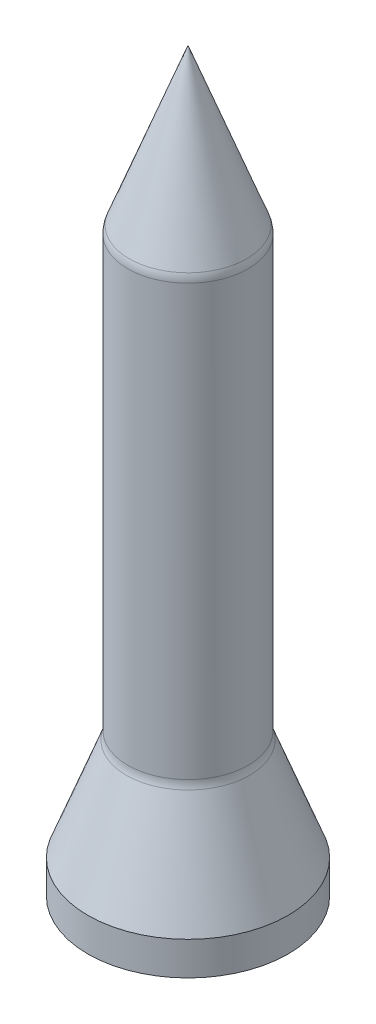
SolidWorks part; units mm, degrees
ref_plane "Front Plane" through (0, 0, 0) normal (0, 0, 1) x (1, 0, 0)
ref_plane "Top Plane" through (0, 0, 0) normal (0, 1, 0) x (1, 0, 0)
ref_plane "Right Plane" through (0, 0, 0) normal (1, 0, 0) x (0, 0, -1)
sketch "Sketch1" plane through (0, 0, 0) normal (1, 0, 0) x (0, 0, -1)
  line L0 (127, 271.5) -> (635, 271.5) construction
  line L2 (641.0575, 134.1986) -> (641.0575, 95.4179)
  line L3 (641.0575, 95.4179) -> (637.5195, 86.0454)
  line L4 (637.5195, 86.0454) -> (637.5195, 83.0829)
  line L8 (646.384, 148.3091) -> (646.384, 78.8711) construction
  line L9 (646.384, 148.3091) -> (646.384, 78.8711)
  line L10 (637.5195, 83.0829) -> (646.207, 83.0829)
  line L11 (641.0575, 134.1986) -> (646.3549, 148.232)
  line L12 (646.3549, 148.232) -> (646.207, 83.0829)
revolve "Revolve1" add sketch "Sketch1" angle 360 about L8
fillet "Fillet1" radius 2 1 edges at (0, 95.4179, -641.0575)
fillet "Fillet2" radius 2 1 edges at (0, 134.1986, -641.0575)
